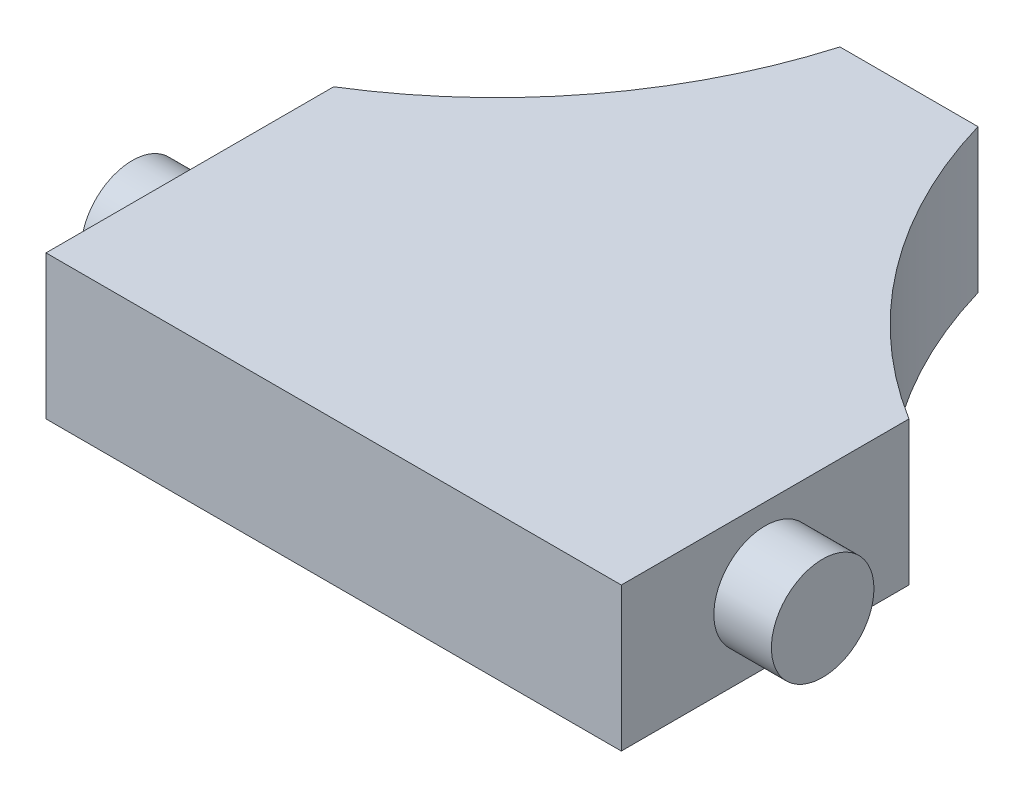
SolidWorks part; units mm, degrees
ref_plane "Alzado" through (0, 0, 0) normal (0, 0, 1) x (1, 0, 0)
ref_plane "Planta" through (0, 0, 0) normal (0, 1, 0) x (1, 0, 0)
ref_plane "Vista lateral" through (0, 0, 0) normal (1, 0, 0) x (0, 0, -1)
sketch "Croquis1" plane through (0, 0, 0) normal (0, 1, 0) x (1, 0, 0)
  line L0 (50, 0) -> (-50, 0)
  line L1 (-50, 0) -> (-50, 50)
  line L2 (-50, 50) -> (50, 50)
  line L3 (50, 50) -> (50, 0)
  line L4 (0, -55) -> (0, 55) construction
  arc A0 (-50, 0) -> (-12, 50) centre (-96.2895, 74.62) ccw
  arc A1 (50, 0) -> (12, 50) centre (96.2895, 74.62) cw
  point P4 (0, 0)
  point P8 (0, 50)
  dimension "D1" = 100
  dimension "D2" = 50
  dimension "D3" = 12
extrude "Saliente-Extruir1" add sketch "Croquis1" along normal blind 25 contours L0 A1 L2 A0
sketch "Croquis2" plane through (0, 0, 0) normal (0, 0, 1) x (1, 0, 0)
  line L1 (-50, 25) -> (50, 25)
  line L2 (-50, 25) -> (-50, 0)
  line L3 (-50, 0) -> (50, 0)
  line L4 (50, 25) -> (50, 0)
extrude "Saliente-Extruir2" add sketch "Croquis2" along normal blind 50
sketch "Croquis3" plane through (50, 0, 0) normal (1, 0, 0) x (0, 0, -1)
  line L0 (-50, 12.5) -> (0, 12.5) construction
  line L1 (-50, 0) -> (-50, 25) construction
  line L2 (0, 25) -> (0, 0) construction
  circle A0 centre (-25, 12.5) radius 8.9129
extrude "Saliente-Extruir3" add sketch "Croquis3" along normal blind 10
mirror "Simetría1" about plane through (0, 0, 0) normal (1, 0, 0) of "Saliente-Extruir3"
